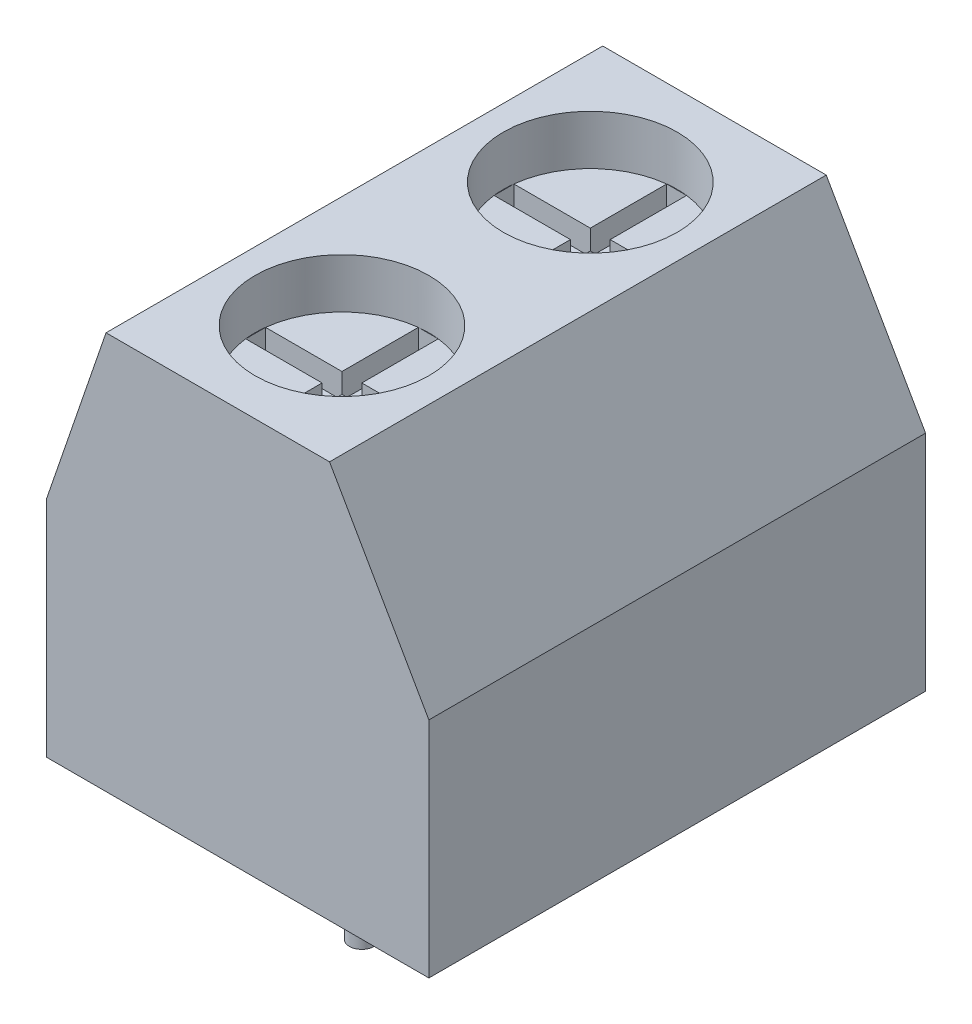
SolidWorks part; units mm, degrees
ref_plane "Plan de face" through (0, 0, 0) normal (0, 0, 1) x (1, 0, 0)
ref_plane "Plan de dessus" through (0, 0, 0) normal (0, 1, 0) x (1, 0, 0)
ref_plane "Plan de droite" through (0, 0, 0) normal (1, 0, 0) x (0, 0, -1)
sketch "Esquisse1" plane through (0, 0, 0) normal (0, 0, 1) x (1, 0, 0)
  line L0 (-7.7, 8) -> (-7.7, 4.5) construction
  line L1 (0, 0) -> (-7.7, 0)
  line L2 (0, 0) -> (0, 8)
  line L3 (0, 8) -> (-7.7, 8)
  line L4 (-7.7, 0) -> (-7.7, 8)
  line L5 (-7.7, 8) -> (-6.5, 8) construction
  line L6 (-6.5, 8) -> (-2, 8) construction
  line L7 (-2, 8) -> (0, 8) construction
  line L8 (0, 8) -> (0, 4.5) construction
  line L9 (-7.7, 4.5) -> (-6.5, 8)
  line L10 (-2, 8) -> (0, 4.5)
  dimension "D1" = 7.7
  dimension "D2" = 8
  dimension "D3" = 1.2
  dimension "D4" = 3.5
  dimension "D5" = 3.5
  dimension "D6" = 2
extrude "Boss.-Extru.2" add sketch "Esquisse1" along normal blind 10 contours L10 L3 L9 L4 L1 L2
sketch "Esquisse2" plane through (-7.7, 0, 0) normal (-1, 0, 0) x (0, 0, 1)
  line L0 (10, 4.5) -> (0, 4.5) construction
  line L1 (0.4, 3.8) -> (4.8, 3.8)
  line L2 (0.4, 3.8) -> (0.4, 0.4)
  line L3 (0.4, 0.4) -> (4.8, 0.4)
  line L4 (4.8, 3.8) -> (4.8, 0.4)
  line L5 (5.2, 3.8) -> (9.6, 3.8)
  line L6 (5.2, 3.8) -> (5.2, 0.4)
  line L7 (5.2, 0.4) -> (9.6, 0.4)
  line L8 (9.6, 3.8) -> (9.6, 0.4)
  line L9 (10, 0) -> (10, 4.5) construction
  line L10 (0, 0) -> (0, 4.5) construction
  line L12 (10, 0) -> (0, 0) construction
  dimension "D1" = 0.7
  dimension "D2" = 0.7
  dimension "D3" = 0.4
  dimension "D4" = 0.4
  dimension "D5" = 0.4
  dimension "D6" = 0.4
  dimension "D7" = 0.4
  dimension "D8" = 4.4
extrude "Enlèv. mat.-Extru.1" cut sketch "Esquisse2" against normal blind 6
sketch "Esquisse3" plane through (0, 0, 0) normal (0, -1, 0) x (-1, 0, 0)
  line L0 (3.85, 0) -> (3.85, -10) construction
  line L1 (0, 0) -> (7.7, 0) construction
  line L2 (0, -10) -> (7.7, -10) construction
  line L3 (3.85, -7.5) -> (3.85, -2.5) construction
  circle A0 centre (3.85, -2.5) radius 0.25
  circle A1 centre (3.85, -7.5) radius 0.25
  point P9 (3.85, -5)
  dimension "D2" = 0.5
  dimension "D3" = 0.5
  dimension "D1" = 5
extrude "Boss.-Extru.3" add sketch "Esquisse3" along normal blind 2.5
sketch "Esquisse5" plane through (0, 8, 0) normal (0, 1, 0) x (1, 0, 0)
  line L0 (-4.25, -10) -> (-4.25, -7.5) construction
  line L1 (-2, -10) -> (-6.5, -10) construction
  line L2 (-4.25, -7.5) -> (-4.25, -2.5) construction
  line L3 (-4.25, -2.5) -> (-4.25, 0) construction
  line L4 (-2, 0) -> (-6.5, 0) construction
  circle A0 centre (-4.25, -7.5) radius 1.75
  circle A1 centre (-4.25, -2.5) radius 1.75
  dimension "D3" = 3.5
  dimension "D4" = 3.5
  dimension "D1" = 2.5
  dimension "D2" = 2.5
extrude "Enlèv. mat.-Extru.2" cut sketch "Esquisse5" against normal blind 1
sketch "Esquisse6" plane through (0, 7, 0) normal (0, 1, 0) x (1, 0, 0)
  line L1 (-4.45, -5.7615) -> (-4.05, -5.7615)
  line L2 (-4.45, -5.7615) -> (-4.45, -9.2385)
  line L3 (-4.45, -9.2385) -> (-4.05, -9.2385)
  line L4 (-4.05, -5.7615) -> (-4.05, -9.2385)
  line L5 (-4.45, -5.7615) -> (-4.05, -9.2385) construction
  line L6 (-4.45, -9.2385) -> (-4.05, -5.7615) construction
  line L7 (-5.9885, -7.7) -> (-2.5115, -7.7)
  line L8 (-5.9885, -7.7) -> (-5.9885, -7.3)
  line L9 (-5.9885, -7.3) -> (-2.5115, -7.3)
  line L10 (-2.5115, -7.7) -> (-2.5115, -7.3)
  line L11 (-5.9885, -7.7) -> (-2.5115, -7.3) construction
  line L12 (-5.9885, -7.3) -> (-2.5115, -7.7) construction
  line L13 (-4.05, -0.7615) -> (-4.45, -0.7615)
  line L14 (-4.05, -0.7615) -> (-4.05, -4.2385)
  line L15 (-4.05, -4.2385) -> (-4.45, -4.2385)
  line L16 (-4.45, -0.7615) -> (-4.45, -4.2385)
  line L17 (-4.05, -0.7615) -> (-4.45, -4.2385) construction
  line L18 (-4.05, -4.2385) -> (-4.45, -0.7615) construction
  line L19 (-5.9885, -2.3) -> (-2.5115, -2.3)
  line L20 (-5.9885, -2.3) -> (-5.9885, -2.7)
  line L21 (-5.9885, -2.7) -> (-2.5115, -2.7)
  line L22 (-2.5115, -2.3) -> (-2.5115, -2.7)
  line L23 (-5.9885, -2.3) -> (-2.5115, -2.7) construction
  line L24 (-5.9885, -2.7) -> (-2.5115, -2.3) construction
  circle A0 centre (-4.25, -7.5) radius 1.75 construction
  circle A1 centre (-4.25, -2.5) radius 1.75 construction
  circle A2 centre (-4.25, -2.5) radius 1.75 construction
  point P0 (-4.25, -7.5)
  point P8 (-4.25, -7.5)
  point P13 (-4.25, -2.5)
  point P21 (-4.25, -2.5)
  dimension "D1" = 0.4
  dimension "D2" = 0.4
  dimension "D3" = 0.4
  dimension "D4" = 0.4
extrude "Enlèv. mat.-Extru.3" cut sketch "Esquisse6" against normal blind 0.5 contours L9 L8 L7 L2 | L7 L2 L3 L4 | L7 L10 L9 L4 | L2 L9 L4 L1 | L9 L2 L7 L4 | L21 L16 L15 L14 | L16 L21 L14 L19 | L22 L19 L14 L21 | L16 L19 L14 L13 | L20 L21 L16 L19
